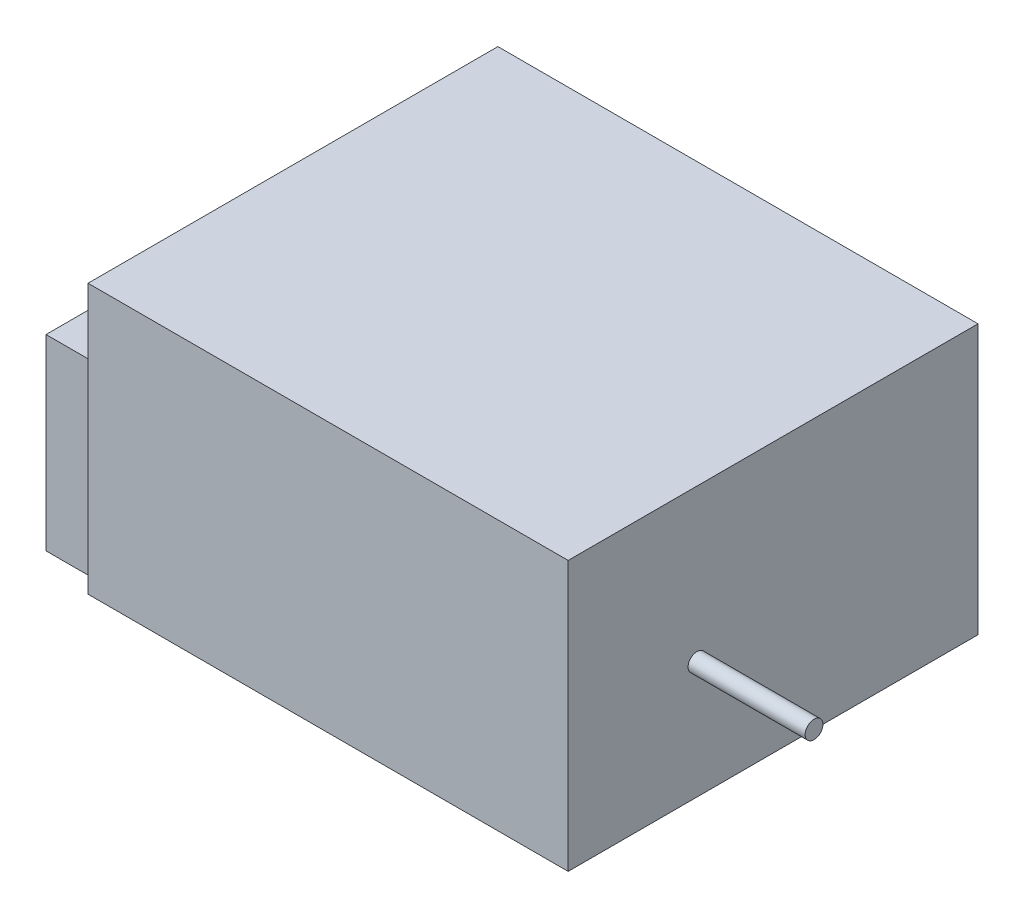
SolidWorks part; units mm, degrees
ref_plane "Front Plane" through (0, 0, 0) normal (0, 0, 1) x (1, 0, 0)
ref_plane "Top Plane" through (0, 0, 0) normal (0, 1, 0) x (1, 0, 0)
ref_plane "Right Plane" through (0, 0, 0) normal (1, 0, 0) x (0, 0, -1)
sketch "Sketch1" plane through (0, 0, 0) normal (0, 1, 0) x (1, 0, 0)
  line L1 (-52.07, 44.45) -> (52.07, 44.45)
  line L2 (-52.07, 44.45) -> (-52.07, -44.45)
  line L3 (-52.07, -44.45) -> (52.07, -44.45)
  line L4 (52.07, 44.45) -> (52.07, -44.45)
  line L5 (-52.07, 44.45) -> (52.07, -44.45) construction
  line L6 (-52.07, -44.45) -> (52.07, 44.45) construction
  point P4 (0, 0)
  dimension "D1" = 88.9
  dimension "D2" = 104.14
extrude "Boss-Extrude1" add sketch "Sketch1" along normal blind 58.42
sketch "Sketch2" plane through (-52.07, 0, 0) normal (-1, 0, 0) x (0, 0, 1)
  line L0 (-44.45, 0) -> (44.45, 0) construction
  line L1 (0.2246, 0) -> (40.8646, 0)
  line L2 (0.2246, 0) -> (0.2246, 40.64)
  line L3 (0.2246, 40.64) -> (40.8646, 40.64)
  line L4 (40.8646, 0) -> (40.8646, 40.64)
  line L5 (0.2246, 0) -> (40.8646, 40.64) construction
  line L6 (0.2246, 40.64) -> (40.8646, 0) construction
  point P4 (20.5446, 20.32)
  dimension "D1" = 40.64
  dimension "D2" = 40.64
extrude "Boss-Extrude2" add sketch "Sketch2" along normal blind 12.7
sketch "Sketch3" plane through (52.07, 0, 0) normal (1, 0, 0) x (0, 0, -1)
  line L0 (-44.45, 0) -> (44.45, 0) construction
  line L1 (-44.45, 58.42) -> (-44.45, 0) construction
  circle A0 centre (-16.51, 25.4) radius 1.9275
  dimension "D1" = 25.4
  dimension "D2" = 27.94
extrude "Boss-Extrude3" add sketch "Sketch3" along normal blind 25.4
sketch "Sketch4" plane through (-52.07, 0, 0) normal (-1, 0, 0) x (0, 0, 1)
  line L0 (-44.45, 0) -> (0.2246, 0) construction
  line L1 (-44.45, 58.42) -> (-44.45, 0) construction
  circle A0 centre (-39.37, 25.4) radius 2.6821
  dimension "D1" = 25.4
  dimension "D2" = 5.08
extrude "Boss-Extrude4" add sketch "Sketch4" along normal blind 25.4
